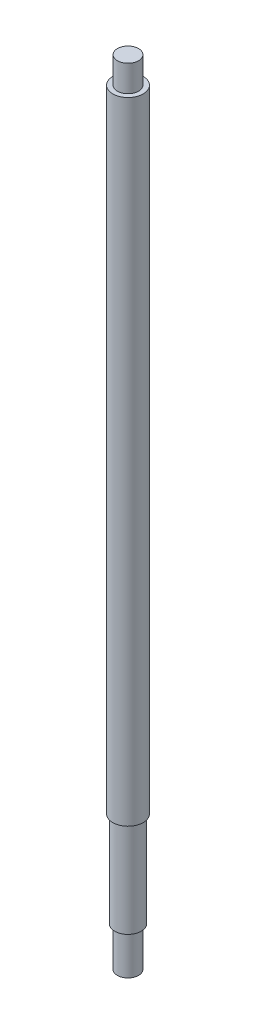
SolidWorks part; units mm, degrees
ref_plane "Front Plane" through (0, 0, 0) normal (0, 0, 1) x (1, 0, 0)
ref_plane "Top Plane" through (0, 0, 0) normal (0, 1, 0) x (1, 0, 0)
ref_plane "Right Plane" through (0, 0, 0) normal (1, 0, 0) x (0, 0, -1)
sketch "Sketch1" plane through (0, 0, 0) normal (0, 0, 1) x (1, 0, 0)
  line L0 (0, 24.0146) -> (0, -17.185) construction
  line L1 (0, 0) -> (4, 0)
  line L2 (4, 0) -> (4, -10)
  line L3 (4, -10) -> (5.75, -10)
  line L4 (5.75, -10) -> (5.75, -249)
  line L5 (5.75, -249) -> (5, -249)
  line L6 (5, -249) -> (5, -285)
  line L7 (5, -285) -> (4, -285)
  line L8 (4, -285) -> (4, -300)
  line L9 (4, -300) -> (0, -300)
  line L10 (0, -300) -> (0, 0)
  dimension "D1" = 300
  dimension "D2" = 10
  dimension "D3" = 15
  dimension "D4" = 36
  dimension "D5" = 11.5
  dimension "D6" = 10
  dimension "D7" = 8
  dimension "D8" = 8
revolve "Revolve1" add sketch "Sketch1" angle 360 about L0
cosmetic thread "Cosmetic Thread1"
